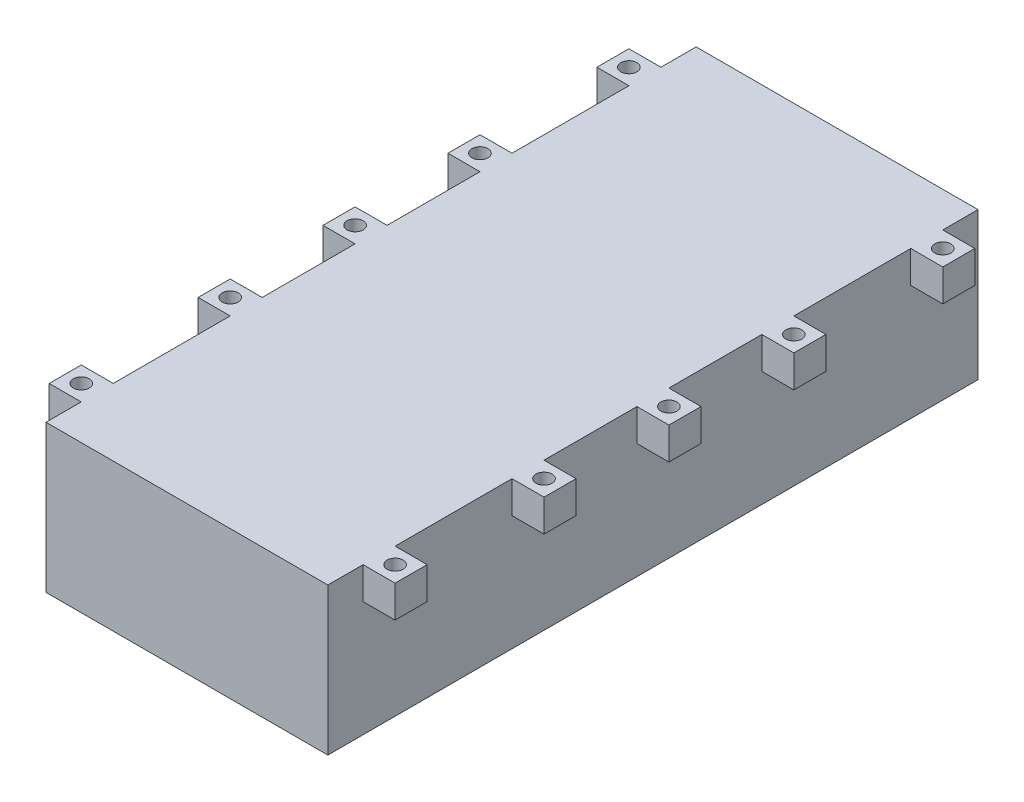
SolidWorks part; units mm, degrees
ref_plane "Front Plane" through (0, 0, 0) normal (0, 0, 1) x (1, 0, 0)
ref_plane "Top Plane" through (0, 0, 0) normal (0, 1, 0) x (1, 0, 0)
ref_plane "Right Plane" through (0, 0, 0) normal (1, 0, 0) x (0, 0, -1)
sketch "Sketch1" plane through (0, 0, 0) normal (0, 0, 1) x (1, 0, 0)
  line L0 (-44, 0) -> (-44, -3) construction
  line L1 (0, 0) -> (-88, 0)
  line L2 (0, 0) -> (0, -46)
  line L3 (0, -46) -> (-88, -46)
  line L4 (-88, 0) -> (-88, -46)
  line L5 (-44, -3) -> (-85, -3) construction
  line L7 (-85, -3) -> (-3, -3)
  line L8 (-85, -3) -> (-85, -43)
  line L9 (-85, -43) -> (-3, -43)
  line L10 (-3, -3) -> (-3, -43)
  dimension "D1" = 88
  dimension "D2" = 46
  dimension "D3" = 3
  dimension "D4" = 41
  dimension "D5" = 40
  dimension "D6" = 82
extrude "Boss-Extrude1" add sketch "Sketch1" along normal blind 3 contours L10 L7 L8 L9 | L1 L4 L3 L2 L7 L10 L9 L8
sketch "Sketch3" plane through (0, 0, 0) normal (0, 0, -1) x (-1, 0, 0)
  line L0 (44, 0) -> (44, -3) construction
  line L1 (0, 0) -> (88, 0)
  line L2 (0, 0) -> (0, -46)
  line L3 (0, -46) -> (88, -46)
  line L4 (88, 0) -> (88, -46)
  line L5 (24, -3) -> (43, -3)
  line L6 (43, -1.5) -> (45, -1.5)
  line L7 (3, -3) -> (22, -3)
  line L8 (3, -3) -> (3, -43)
  line L9 (3, -43) -> (22, -43)
  line L10 (85, -3) -> (85, -43)
  line L11 (43, -1.5) -> (43, -3)
  line L12 (45, -1.5) -> (45, -3)
  line L13 (44, -1.5) -> (45, -1.5) construction
  line L14 (44, -1.5) -> (45, -1.507) construction
  line L15 (44, -1.5) -> (45, -1.5) construction
  line L16 (44, -1.5) -> (65, -1.5) construction
  line L17 (44, -1.5) -> (23, -1.5) construction
  line L18 (66, -1.5) -> (64, -1.5)
  line L19 (64, -1.5) -> (64, -3)
  line L20 (66, -1.5) -> (66, -3)
  line L21 (22, -1.5) -> (24, -1.5)
  line L22 (22, -1.5) -> (22, -3)
  line L23 (24, -1.5) -> (24, -3)
  line L24 (3, -23) -> (85, -23) construction
  line L25 (64, -44.5) -> (64, -43)
  line L26 (66, -44.5) -> (66, -43)
  line L27 (66, -44.5) -> (64, -44.5)
  line L28 (45, -44.5) -> (45, -43)
  line L29 (43, -44.5) -> (45, -44.5)
  line L30 (43, -44.5) -> (43, -43)
  line L31 (24, -44.5) -> (24, -43)
  line L32 (22, -44.5) -> (24, -44.5)
  line L33 (22, -44.5) -> (22, -43)
  line L34 (24, -43) -> (43, -43)
  line L35 (45, -43) -> (64, -43)
  line L36 (66, -43) -> (85, -43)
  line L37 (66, -3) -> (85, -3)
  line L38 (45, -3) -> (64, -3)
  line L39 (43, -3) -> (24, -3) construction
  line L40 (22, -3) -> (3, -3) construction
  point P15 (44, -1.5)
  point P24 (65, -1.5)
  point P29 (23, -1.5)
  dimension "D1" = 3
  dimension "D2" = 41
  dimension "D3" = 40
  dimension "D4" = 82
  dimension "D5" = 2
  dimension "D6" = 21
  dimension "D7" = 21
  dimension "D8" = 2
  dimension "D9" = 2
extrude "Boss-Extrude2" add sketch "Sketch3" along normal blind 200
sketch "Sketch6" plane through (0, 0, 0) normal (0, 1, 0) x (1, 0, 0)
  line L0 (-44, 200) -> (-44, -3) construction
  line L1 (-88, 200) -> (0, 200) construction
  line L2 (0, -3) -> (-88, -3) construction
  line L3 (-44, 98.5) -> (-88, 98.5) construction
  line L4 (-88, -3) -> (-88, 200) construction
  line L5 (-88, 98.5) -> (-88, 93.5) construction
  line L6 (-88, -3) -> (-88, 200) construction
  line L7 (0, -3) -> (0, 200) construction
  line L8 (-88, 93.5) -> (-98, 93.5)
  line L9 (-88, 93.5) -> (-88, 103.5)
  line L10 (-88, 103.5) -> (-98, 103.5)
  line L11 (-98, 93.5) -> (-98, 103.5)
  line L12 (0, 93.5) -> (10, 93.5)
  line L13 (0, 93.5) -> (0, 103.5)
  line L14 (0, 103.5) -> (10, 103.5)
  line L15 (10, 93.5) -> (10, 103.5)
  line L16 (-88, 142.5) -> (-98, 142.5)
  line L17 (-98, 132.5) -> (-98, 142.5)
  line L18 (-88, 132.5) -> (-98, 132.5)
  line L19 (-88, 132.5) -> (-88, 142.5)
  line L20 (0, 132.5) -> (10, 132.5)
  line L21 (10, 132.5) -> (10, 142.5)
  line L22 (0, 142.5) -> (10, 142.5)
  line L23 (0, 132.5) -> (0, 142.5)
  line L24 (-88, 54.5) -> (-98, 54.5)
  line L25 (-98, 54.5) -> (-98, 64.5)
  line L26 (-88, 64.5) -> (-98, 64.5)
  line L27 (-88, 54.5) -> (-88, 64.5)
  line L28 (0, 54.5) -> (0, 64.5)
  line L29 (0, 54.5) -> (10, 54.5)
  line L30 (10, 54.5) -> (10, 64.5)
  line L31 (0, 64.5) -> (10, 64.5)
  line L32 (-88, 8) -> (-98, 8)
  line L33 (-98, 8) -> (-98, 18)
  line L34 (-88, 18) -> (-98, 18)
  line L35 (-88, 8) -> (-88, 18)
  line L36 (0, 8) -> (0, 18)
  line L37 (0, 18) -> (10, 18)
  line L38 (10, 8) -> (10, 18)
  line L39 (0, 8) -> (10, 8)
  line L40 (0, 179) -> (10, 179)
  line L41 (0, 179) -> (0, 189)
  line L42 (0, 189) -> (10, 189)
  line L43 (10, 179) -> (10, 189)
  line L44 (-88, 179) -> (-98, 179)
  line L45 (-98, 179) -> (-98, 189)
  line L46 (-88, 189) -> (-98, 189)
  line L47 (-88, 179) -> (-88, 189)
  line L48 (-93, 8) -> (-93, 18) construction
  line L49 (-93, 18) -> (-93, 54.5) construction
  line L50 (-93, 54.5) -> (-93, 64.5) construction
  line L51 (-93, 64.5) -> (-93, 93.5) construction
  line L52 (-93, 93.5) -> (-93, 103.5) construction
  line L53 (-93, 103.5) -> (-93, 132.5) construction
  line L54 (-93, 132.5) -> (-93, 142.5) construction
  line L55 (-93, 142.5) -> (-93, 179) construction
  line L56 (-93, 179) -> (-93, 189) construction
  line L57 (-93, 189) -> (5, 189) construction
  line L58 (5, 189) -> (5, 179) construction
  line L59 (5, 179) -> (5, 142.5) construction
  line L60 (5, 142.5) -> (5, 132.5) construction
  line L61 (5, 132.5) -> (5, 103.5) construction
  line L62 (5, 103.5) -> (5, 93.5) construction
  line L63 (5, 93.5) -> (5, 64.5) construction
  line L64 (5, 64.5) -> (5, 54.5) construction
  line L65 (5, 54.5) -> (5, 18) construction
  line L66 (5, 18) -> (5, 8) construction
  circle A0 centre (5, 13) radius 2.5
  circle A1 centre (5, 59.5) radius 2.5
  circle A2 centre (5, 98.5) radius 2.5
  circle A3 centre (5, 137.5) radius 2.5
  circle A4 centre (5, 184) radius 2.5
  circle A6 centre (-93, 137.5) radius 2.5
  circle A7 centre (-93, 98.5) radius 2.5
  circle A8 centre (-93, 13) radius 2.5
  circle A9 centre (-93, 59.5) radius 2.5
  circle A10 centre (-93, 184) radius 2.5
  dimension "D10" = 5
  dimension "D1" = 5
  dimension "D2" = 10
  dimension "D3" = 10
  dimension "D4" = 10
  dimension "D5" = 10
  dimension "D6" = 2
  dimension "D7" = 2
  dimension "D8" = 2
  dimension "D9" = 2
extrude "Boss-Extrude4" add sketch "Sketch6" against normal blind 10
